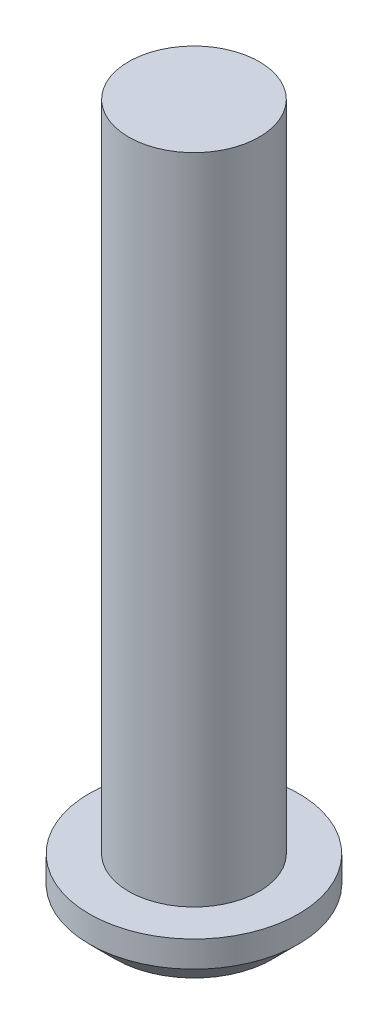
SolidWorks part; units mm, degrees
ref_plane "Front Plane" through (0, 0, 0) normal (0, 0, 1) x (1, 0, 0)
ref_plane "Top Plane" through (0, 0, 0) normal (0, 1, 0) x (1, 0, 0)
ref_plane "Right Plane" through (0, 0, 0) normal (1, 0, 0) x (0, 0, -1)
sketch "Sketch1" plane through (0, 0, 0) normal (0, 1, 0) x (1, 0, 0)
  circle A1 centre (0, 0) radius 4
  dimension "D2" = 8
extrude "Boss-Extrude1" add sketch "Sketch1" along normal blind 2
sketch "Sketch2" plane through (0, 2, 0) normal (0, 1, 0) x (1, 0, 0)
  circle A0 centre (0, 0) radius 2.5
  dimension "D1" = 5
extrude "Boss-Extrude2" add sketch "Sketch2" along normal blind 25
hole_wizard "M2 Tapped Hole1" positions "Sketch4" profile "Sketch5" tap size "M2" standard "GB"
sketch "Sketch4" plane through (0, 0, 0) normal (0, -1, 0) x (-1, 0, 0)
  point P0 (0, 0)
cosmetic thread "Hole Thread1" parameters "D1"=6, "D2"=2
sketch "Sketch5" plane through (0, 0, 0) normal (1, 0, 0) x (0, 0, -1)
  line L0 (0, 0) -> (0, 8.4807)
  line L1 (0, 8.4807) -> (0.8, 8)
  line L2 (0.8, 8) -> (0.8, 0.225)
  line L3 (0.8, 0.225) -> (1.025, 0)
  line L5 (1.025, 0) -> (0, 0)
  line L6 (-0.8, 0.225) -> (-1.025, 0) construction
  line L10 (0, 8.4807) -> (-0.8, 8) construction
  line L11 (0, -6.35) -> (0, 107.95) construction
  dimension "Tap Drill Dia." = 1.6
  dimension "Tap Drill Depth" = 8
  dimension "Near C'Sink Dia." = 2.05
  dimension "Near C'Sink Angle" = 90
  dimension "Drill Angle" = 118
chamfer "Chamfer1" distance 1 angle 45 1 edges at (0, 0, 4)
